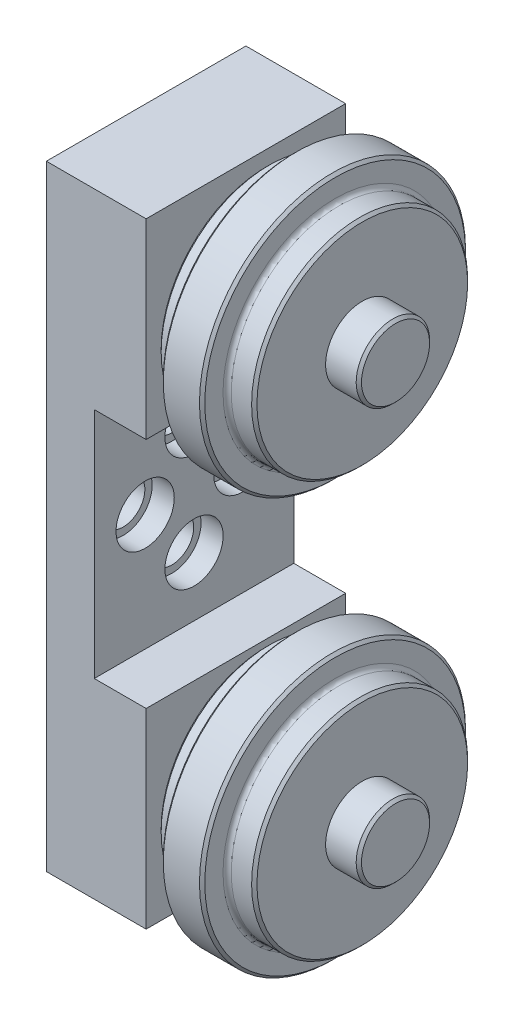
SolidWorks part; units mm, degrees
ref_plane "Front" through (0, 0, 0) normal (0, 0, 1) x (1, 0, 0)
ref_plane "Top" through (0, 0, 0) normal (0, 1, 0) x (1, 0, 0)
ref_plane "Right" through (0, 0, 0) normal (1, 0, 0) x (0, 0, -1)
sketch "Sketch2" plane through (0, 0, 0) normal (0, 0, 1) x (1, 0, 0)
  line L0 (3.9624, 61.0997) -> (3.9624, 64.5795)
  line L1 (3.9624, 64.5795) -> (3.4544, 65.0875)
  line L2 (3.4544, 65.0875) -> (-3.4544, 65.0875)
  line L3 (-3.4544, 65.0875) -> (-3.9624, 64.5795)
  line L4 (-3.9624, 64.5795) -> (-3.9624, 61.0997)
  line L5 (-4.7498, 60.3123) -> (-8.636, 60.3123)
  line L6 (-8.636, 60.3123) -> (-9.144, 59.8043)
  line L7 (-9.144, 59.8043) -> (-9.144, 43.6499)
  line L8 (0, 65.0875) -> (0, 14.2875) construction
  line L9 (-9.655, 43.6499) -> (-9.144, 43.6499)
  line L10 (9.144, 46.6979) -> (9.144, 32.6771) construction
  line L11 (9.144, 46.6979) -> (9.144, 59.8043)
  line L12 (9.144, 59.8043) -> (8.636, 60.3123)
  line L13 (8.636, 60.3123) -> (4.7498, 60.3123)
  line L14 (6.6929, 60.3123) -> (6.6929, 19.0627) construction
  line L15 (-11.368, 49.2125) -> (-11.368, 30.1625) construction
  line L16 (-13.081, 43.6499) -> (-22.098, 43.6499)
  line L17 (-22.098, 43.6499) -> (-22.606, 43.1419)
  line L18 (-22.606, 43.1419) -> (-22.606, 39.6875)
  line L19 (-17.5895, 43.6499) -> (-17.5895, 35.7251) construction
  line L20 (0, 39.6875) -> (0, -39.6875) construction
  line L29 (15.494, 39.6875) -> (15.494, 46.1899)
  line L30 (15.494, 46.1899) -> (14.986, 46.6979)
  line L31 (14.986, 46.6979) -> (9.144, 46.6979)
  line L37 (-9.655, 43.6499) -> (-9.655, 49.2125)
  line L38 (-9.655, 49.2125) -> (-13.081, 49.2125)
  line L39 (-13.081, 49.2125) -> (-13.081, 43.6499)
  line L62 (-22.606, 39.6875) -> (15.494, 39.6875)
  arc A0 (-4.7498, 60.3123) -> (-3.9624, 61.0997) centre (-4.7498, 61.0997) ccw
  arc A1 (3.9624, 61.0997) -> (4.7498, 60.3123) centre (4.7498, 61.0997) ccw
  point P11 (9.144, 39.6875)
  point P12 (0, 39.6875)
  point P22 (6.6929, 39.6875)
  point P25 (-11.368, 39.6875)
  point P30 (-17.5895, 39.6875)
  dimension "D3" = 0.7874
  dimension "D1" = 45
  dimension "D2" = 0.508
  dimension "Wheel Thick 1" = 7.9248
  dimension "Wheel Thick 2" = 18.288
  dimension "D4" = 0.511
  dimension "Wheel Dia 1" = 50.8
  dimension "Wheel Dia 3" = 14.0208
  dimension "Wheel Dia 2" = 41.2496
  dimension "Wheel Dia 4" = 19.05
  dimension "Wheel Dia 5" = 7.9248
  dimension "Wheel Wd 1" = 28.575
  dimension "Nose Wd" = 6.35
  dimension "Wheel Wd 2" = 38.1
  dimension "Center-To-Center" = 79.375
revolve "Revolve1" add sketch "Sketch2" angle 360 mid plane about L62
sketch "Sketch1" plane through (0, 0, 0) normal (0, 0, 1) x (1, 0, 0)
  line L0 (-32.131, 58.7375) -> (-32.131, -58.7375)
  line L1 (-32.131, -58.7375) -> (-13.081, -58.7375)
  line L2 (-13.081, -58.7375) -> (-13.081, -22.2377)
  line L3 (-13.081, -22.2377) -> (-22.987, -22.2377)
  line L4 (-22.987, -22.2377) -> (-22.987, 22.2377)
  line L5 (-22.987, 22.2377) -> (-13.081, 22.2377)
  line L6 (-13.081, 22.2377) -> (-13.081, 58.7375)
  line L7 (-13.081, 58.7375) -> (-32.131, 58.7375)
  line L9 (-13.081, 49.2125) -> (-13.081, 30.1625) construction
  point P8 (-32.131, 0)
  dimension "Body Dp" = 19.05
  dimension "Body Ht" = 117.475
  dimension "Neck Wd" = 9.144
  dimension "Nose Ht" = 36.4998
extrude "Boss-Extrude1" add sketch "Sketch1" along normal mid plane 38.1 separate body
sketch "Sketch3" plane through (-32.131, 0, 0) normal (-1, 0, 0) x (0, 0, 1)
  line L0 (0, 39.6875) -> (0, -39.6875) construction
  circle A0 centre (0, 39.6875) radius 3.9624
  circle A1 centre (0, -39.6875) radius 3.9624
  circle A2 centre (0, 39.6875) radius 3.9624 construction
extrude "Cut-Extrude1" cut sketch "Sketch3" against normal through all
mirror "Mirror1" about plane through (0, 0, 0) normal (0, 1, 0) of bodies 109
sketch "Sketch4" plane through (-22.987, 0, 0) normal (1, 0, 0) x (0, 0, -1)
  line L0 (0, 10.922) -> (0, -10.922) construction
  line L2 (-9.3345, 0) -> (9.3345, 0) construction
  circle A0 centre (0, 10.922) radius 4.1656
  circle A1 centre (0, -10.922) radius 4.1656
  circle A2 centre (-9.3345, 0) radius 4.1656
  circle A3 centre (9.3345, 0) radius 4.1656
  dimension "Inner Dia" = 8.3312
  dimension "Holes Vert" = 21.844
  dimension "Holes Hor" = 18.669
extrude "Cut-Extrude2" cut sketch "Sketch4" against normal through all
sketch "Sketch5" plane through (-22.987, 0, 0) normal (1, 0, 0) x (0, 0, -1)
  circle A0 centre (0, 10.922) radius 5.5626
  circle A1 centre (9.3345, 0) radius 5.5626
  circle A2 centre (-9.3345, 0) radius 5.5626
  circle A3 centre (0, -10.922) radius 5.5626
  dimension "Outer Dia" = 11.1252
extrude "Cut-Extrude3" cut sketch "Sketch5" against normal blind 4.2164
sketch "Sketch6" plane through (0, 0, 0) normal (0, 0, 1) x (1, 0, 0)
  line L0 (-27.2034, -5.5626) -> (-22.987, -5.5626) construction
  line L1 (-32.131, -4.1656) -> (-27.2034, -4.1656) construction
  line L2 (-27.2034, -5.5626) -> (-27.2034, 5.5626) construction
  line L3 (-22.987, 5.5626) -> (-27.2034, 5.5626) construction
  line L4 (-27.2034, 4.1656) -> (-32.131, 4.1656) construction
  line L5 (-27.2034, -5.5626) -> (-22.987, -5.5626)
  line L6 (-32.131, -4.1656) -> (-27.2034, -4.1656)
  line L7 (-27.2034, -5.5626) -> (-27.2034, 5.5626)
  line L8 (-22.987, 5.5626) -> (-27.2034, 5.5626)
  line L9 (-27.2034, 4.1656) -> (-32.131, 4.1656)
